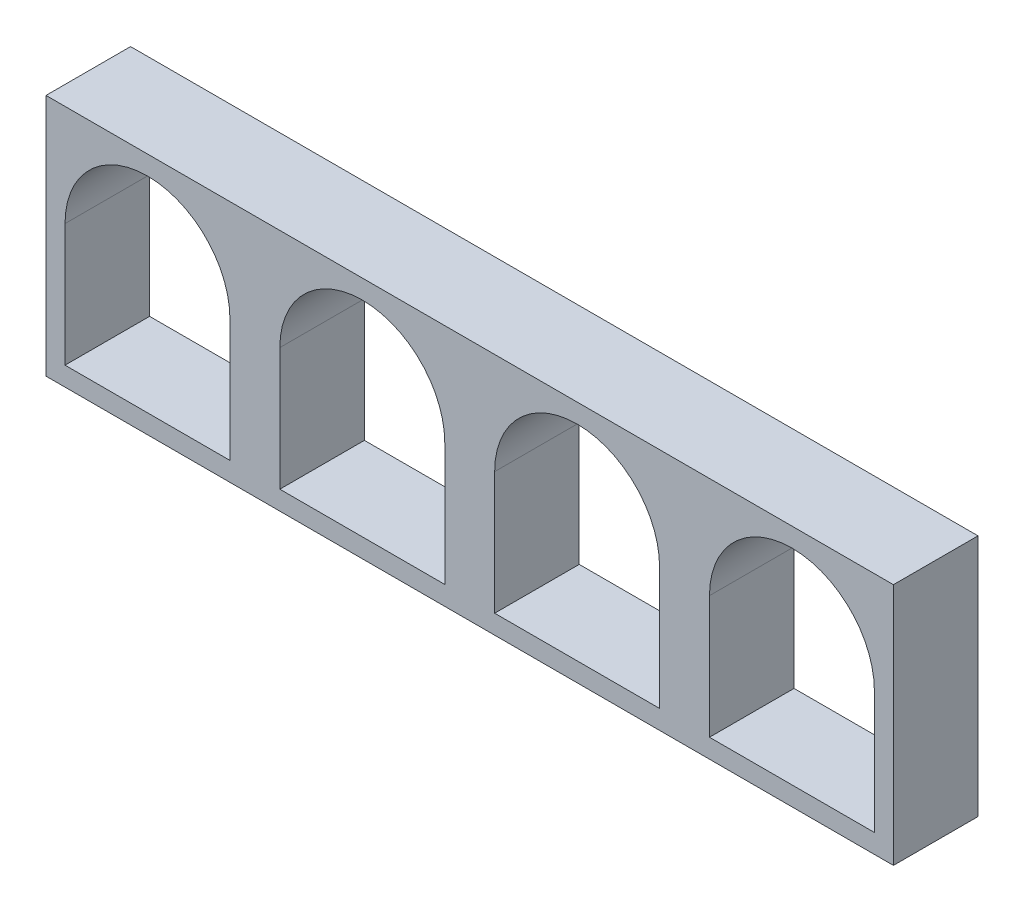
SolidWorks part; units mm, degrees
ref_plane "Front Plane" through (0, 0, 0) normal (0, 0, 1) x (1, 0, 0)
ref_plane "Top Plane" through (0, 0, 0) normal (0, 1, 0) x (1, 0, 0)
ref_plane "Right Plane" through (0, 0, 0) normal (1, 0, 0) x (0, 0, -1)
sketch "Sketch1" plane through (0, 0, 0) normal (0, 0, 1) x (1, 0, 0)
  line L0 (-126.997, -0.8718) -> (-147.7542, 57.5482)
  line L1 (-147.7542, 57.5482) -> (-63.9342, 128.6682)
  line L2 (-63.9342, 128.6682) -> (-63.9342, 105.8082)
  line L3 (-63.9342, 105.8082) -> (-18.2142, 85.4882)
  line L6 (150.6958, 58.8182) -> (379.2958, 58.8182)
  line L8 (415.5478, 62.0264) -> (456.6371, 20.7182)
  line L11 (167.0771, -91.3926) -> (70.5571, -106.6326)
  line L12 (70.5571, -106.6326) -> (-24.0534, -76.8021)
  line L13 (-27.8723, -76.8021) -> (-118.0334, -105.2297)
  line L27 (-25.9629, -76.2) -> (-25.9629, -57.2761) construction
  line L28 (-125.1515, -102.8058) -> (-152.9629, -62.924)
  line L29 (-153.4885, -56.5641) -> (-126.997, -0.8718)
  line L30 (-152.397, -0.8718) -> (-126.997, -0.8718) construction
  line L31 (-18.2142, 85.4882) -> (70.6858, 85.4882)
  line L33 (379.2958, 58.8182) -> (410.0265, 63.8159)
  line L34 (143.2406, -36.5685) -> (167.0771, -91.3926)
  line L35 (-139.0572, -82.8649) -> (-122.3896, -71.2419) construction
  line L40 (-75.6429, -26.15) -> (-5.6429, -26.15)
  line L41 (-75.6429, -26.15) -> (-75.6429, -57.15)
  line L46 (-75.6429, -57.15) -> (-5.6429, -57.15)
  line L47 (-5.6429, -26.15) -> (-5.6429, -57.15)
  line L48 (-131.8821, -41.1959) -> (-97.4763, -90.5342)
  line L49 (-131.8821, -41.1959) -> (-139.5925, -46.5727)
  line L50 (-139.5925, -46.5727) -> (-105.1867, -95.911)
  line L51 (-97.4763, -90.5342) -> (-105.1867, -95.911)
  line L52 (-18.2142, 65.1682) -> (45.2858, 65.1682) construction
  line L53 (379.2958, 46.1182) -> (294.237, 46.1182) construction
  line L58 (369.2958, 31.1182) -> (389.2958, 31.1182)
  line L59 (369.2958, 31.1182) -> (369.2958, 46.1182)
  line L61 (389.2958, 31.1182) -> (389.2958, 46.1182)
  line L62 (343.8958, 31.1182) -> (343.8958, 46.1182)
  line L63 (363.8958, 31.1182) -> (363.8958, 46.1182)
  line L64 (343.8958, 31.1182) -> (363.8958, 31.1182)
  line L65 (318.4958, 31.1182) -> (318.4958, 46.1182)
  line L66 (338.4958, 31.1182) -> (338.4958, 46.1182)
  line L67 (318.4958, 31.1182) -> (338.4958, 31.1182)
  line L68 (293.0958, 31.1182) -> (293.0958, 46.1182)
  line L69 (313.0958, 31.1182) -> (313.0958, 46.1182)
  line L70 (293.0958, 31.1182) -> (313.0958, 31.1182)
  arc A8 (-118.0334, -105.2297) -> (-125.1515, -102.8058) centre (-119.9429, -99.1736) cw
  arc A9 (-152.9629, -62.924) -> (-153.4885, -56.5641) centre (-147.7542, -59.2918) cw
  arc A10 (144.2463, -29.8998) -> (244.3252, 22.4234) centre (259.8701, -129.1817) cw
  arc A12 (244.3252, 22.4234) -> (456.6371, 20.7182) centre (342.7765, -937.7424) cw
  arc A18 (74.4958, 84.2182) -> (150.6958, 58.8182) centre (150.6958, 185.8182) ccw
  arc A19 (70.6858, 85.4882) -> (74.4958, 84.2182) centre (70.6858, 79.1382) cw
  arc A20 (144.2463, -29.8998) -> (143.2406, -36.5685) centre (149.0639, -34.0366) ccw
  arc A21 (-24.0534, -76.8021) -> (-27.8723, -76.8021) centre (-25.9629, -82.8582) ccw
  arc A22 (415.5478, 62.0264) -> (410.0265, 63.8159) centre (411.0458, 57.5482) ccw
  circle A28 centre (-70.2842, 115.9682) radius 2
  circle A29 centre (-142.9282, 55.962) radius 2
  circle A30 centre (-147.7542, -59.2918) radius 2
  circle A31 centre (160.7271, -87.5826) radius 2
  circle A32 centre (70.6858, 79.1382) radius 2
  circle A33 centre (426.1571, 43.4959) radius 2
  circle A34 centre (-18.2142, 65.1682) radius 10
  circle A35 centre (13.5358, 65.1682) radius 10
  circle A36 centre (45.2858, 65.1682) radius 10
  arc A37 (369.2958, 46.1182) -> (389.2958, 46.1182) centre (379.2958, 46.1182) cw
  arc A38 (343.8958, 46.1182) -> (363.8958, 46.1182) centre (353.8958, 46.1182) cw
  arc A39 (318.4958, 46.1182) -> (338.4958, 46.1182) centre (328.4958, 46.1182) cw
  arc A40 (293.0958, 46.1182) -> (313.0958, 46.1182) centre (303.0958, 46.1182) cw
  point P19 (-122.4829, -106.6326)
  point P44 (141.6771, -32.9726)
  point P75 (413.2469, 64.3396)
  dimension "D3" = 6.35
  dimension "D4" = 135
  dimension "D5" = 45
  dimension "D6" = 218.44
  dimension "D16" = 527.05
  dimension "D17" = 70
  dimension "D9" = 33.02
  dimension "D18" = 152.4
  dimension "D24" = 25.4
  dimension "D30" = 127
  dimension "D12" = 965.2
  dimension "D33" = 18.9239
  dimension "D35" = 71.12
  dimension "D14" = 4
  dimension "D37" = 20.32
  dimension "D38" = 6.35
  dimension "D49" = 20
  dimension "D54" = 10
  dimension "D7" = 294.64
  dimension "D8" = 145
  dimension "D10" = 15.24
  dimension "D11" = 127
  dimension "D13" = 22.86
  dimension "D15" = 83.82
  dimension "D19" = 58.42
  dimension "D20" = 107.95
  dimension "D21" = 129.54
  dimension "D22" = 69.85
  dimension "D23" = 31
  dimension "D25" = 129.54
  dimension "D26" = 609.6
  dimension "D27" = 127
  dimension "D28" = 223.52
  dimension "D29" = 320.04
  dimension "D31" = 298.45
  dimension "D32" = 558.8
  dimension "D34" = 76.2
  dimension "D36" = 19.05
  dimension "D39" = 12.7
  dimension "D40" = 5.08
  dimension "D41" = 4.826
  dimension "D42" = 3.81
  dimension "D43" = 6.35
  dimension "D44" = 20.32
  dimension "D45" = 30.48
  dimension "D46" = 60.15
  dimension "D47" = 20.32
  dimension "D48" = 9.4
  dimension "D50" = 20.32
  dimension "D51" = 63.5
  dimension "D52" = 20
  dimension "D53" = 15
  dimension "D55" = 12.7
  dimension "D56" = 4
  dimension "D57" = 25.4
other "AlignGroup1"
sketch "Sketch2" plane through (0, 0, 0) normal (0, 0, 1) x (1, 0, 0)
  line L9 (-9.75, -14.5) -> (-9.75, 0)
  line L10 (9.75, -14.5) -> (9.75, 0)
  line L11 (-9.75, -14.5) -> (9.75, -14.5)
  line L12 (15.65, -14.5) -> (15.65, 0)
  line L13 (35.15, -14.5) -> (35.15, 0)
  line L14 (15.65, -14.5) -> (35.15, -14.5)
  line L15 (41.05, -14.5) -> (41.05, 0)
  line L16 (60.55, -14.5) -> (60.55, 0)
  line L17 (41.05, -14.5) -> (60.55, -14.5)
  line L18 (66.45, -14.5) -> (66.45, 0)
  line L19 (85.95, -14.5) -> (85.95, 0)
  line L20 (66.45, -14.5) -> (85.95, -14.5)
  line L22 (-12, 12) -> (88.2, 12)
  line L23 (-12, 12) -> (-12, -16.75)
  line L24 (-12, -16.75) -> (88.2, -16.75)
  line L25 (88.2, 12) -> (88.2, -16.75)
  arc A3 (-9.75, 0) -> (9.75, 0) centre (0, 0) cw
  arc A4 (15.65, 0) -> (35.15, 0) centre (25.4, 0) cw
  arc A5 (41.05, 0) -> (60.55, 0) centre (50.8, 0) cw
  arc A6 (66.45, 0) -> (85.95, 0) centre (76.2, 0) cw
  point P1 (0, 9.75)
  dimension "D1" = 4
  dimension "D2" = 14.5
  dimension "D3" = 25.4
  dimension "D4" = 2.25
  dimension "D5" = 19.5
  dimension "D6" = 2.25
  dimension "D7" = 2.25
  dimension "D8" = 2.25
extrude "Boss-Extrude1" add sketch "Sketch2" along normal blind 10
